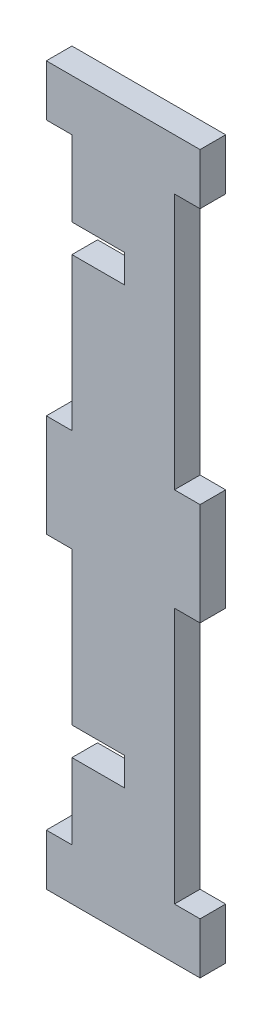
SolidWorks part; units mm, degrees
ref_plane "Front Plane" through (0, 0, 0) normal (0, 0, 1) x (1, 0, 0)
ref_plane "Top Plane" through (0, 0, 0) normal (0, 1, 0) x (1, 0, 0)
ref_plane "Right Plane" through (0, 0, 0) normal (1, 0, 0) x (0, 0, -1)
sketch "Model" plane through (0, 0, 0) normal (0, 0, 1) x (1, 0, 0)
  line L0 (-1086.4543, -202.297) -> (-1086.4543, -212.297)
  line L1 (-1091.4543, -202.297) -> (-1086.4543, -202.297)
  line L2 (-1086.4543, -132.297) -> (-1091.4543, -132.297)
  line L3 (-1116.4543, -212.297) -> (-1116.4543, -202.297)
  line L4 (-1086.4543, -212.297) -> (-1116.4543, -212.297)
  line L5 (-1091.4543, -152.297) -> (-1091.4543, -202.297)
  line L6 (-1086.4543, -152.297) -> (-1091.4543, -152.297)
  line L7 (-1086.4543, -132.297) -> (-1086.4543, -152.297)
  line L8 (-1091.4543, -132.297) -> (-1091.4544, -82.297)
  line L9 (-1091.4544, -82.297) -> (-1086.4544, -82.297)
  line L10 (-1086.4544, -82.297) -> (-1086.4544, -72.297)
  line L11 (-1086.4544, -72.297) -> (-1116.4544, -72.297)
  line L12 (-1116.4544, -72.297) -> (-1116.4544, -82.297)
  line L13 (-1116.4544, -82.297) -> (-1111.4544, -82.297)
  line L14 (-1111.4544, -82.297) -> (-1111.4544, -97.047)
  line L15 (-1101.2044, -97.047) -> (-1111.4544, -97.047)
  line L16 (-1101.2044, -102.547) -> (-1101.2044, -97.047)
  line L17 (-1111.4544, -102.547) -> (-1101.2044, -102.547)
  line L18 (-1111.4544, -102.547) -> (-1111.4543, -132.297)
  line L19 (-1111.4543, -132.297) -> (-1116.4543, -132.297)
  line L20 (-1116.4543, -132.297) -> (-1116.4543, -152.297)
  line L21 (-1111.4543, -152.297) -> (-1116.4543, -152.297)
  line L22 (-1111.4543, -182.047) -> (-1111.4543, -152.297)
  line L23 (-1111.4543, -182.047) -> (-1101.2043, -182.047)
  line L24 (-1101.2043, -182.047) -> (-1101.2043, -187.547)
  line L25 (-1101.2043, -187.547) -> (-1111.4543, -187.547)
  line L26 (-1111.4543, -202.297) -> (-1111.4543, -187.547)
  line L27 (-1116.4543, -202.297) -> (-1111.4543, -202.297)
  line L28 (-1109.4543, -207.297) -> (-1114.4543, -207.297)
  line L29 (-1112.4543, -206.297) -> (-1114.4543, -207.297)
  line L30 (-1112.4543, -208.297) -> (-1114.4543, -207.297)
  line L31 (-1108.4543, -210.3939) -> (-1105.9573, -211.0058)
  line L32 (-1104.1754, -204.7785) -> (-1104.2808, -205.1399)
  line L33 (-1104.5247, -206.337) -> (-1104.4353, -206.3979)
  line L34 (-1104.2777, -206.6414) -> (-1104.4353, -206.3979)
  line L35 (-1104.5249, -205.4413) -> (-1104.4361, -205.381)
  line L36 (-1104.1403, -204.3375) -> (-1104.1754, -204.7785)
  line L37 (-1104.1403, -209.27) -> (-1105.9573, -209.7445)
  line L38 (-1104.1747, -206.9973) -> (-1104.1403, -207.4406)
  line L39 (-1108.4482, -207.4406) -> (-1108.4123, -207.0067)
  line L40 (-1108.1486, -206.3979) -> (-1108.3047, -206.6414)
  line L41 (-1108.4482, -208.4584) -> (-1108.4482, -207.4406)
  line L42 (-1104.2777, -206.6414) -> (-1104.1747, -206.9973)
  line L43 (-1107.9675, -206.3167) -> (-1108.0611, -206.337)
  line L44 (-1104.1403, -207.4406) -> (-1104.1403, -208.4584)
  line L45 (-1107.9675, -206.3167) -> (-1104.6211, -206.3167)
  line L46 (-1104.4361, -205.381) -> (-1104.2808, -205.1399)
  line L47 (-1108.3047, -206.6414) -> (-1108.4123, -207.0067)
  line L48 (-1104.6211, -205.4614) -> (-1104.5249, -205.4413)
  line L49 (-1108.1486, -206.3979) -> (-1108.0611, -206.337)
  line L50 (-1108.4482, -208.4584) -> (-1104.1403, -208.4584)
  line L51 (-1105.9573, -209.7445) -> (-1108.4543, -210.3939)
  line L52 (-1105.9573, -209.7445) -> (-1105.9573, -211.0058)
  line L53 (-1104.6211, -206.3167) -> (-1104.5247, -206.337)
  line L54 (-1104.1754, -203.8965) -> (-1104.1403, -204.3375)
  line L55 (-1106.4279, -203.2337) -> (-1106.3317, -203.2136)
  line L56 (-1104.6211, -203.2136) -> (-1104.5249, -203.2337)
  line L57 (-1108.4482, -203.2885) -> (-1108.4482, -205.4614)
  line L58 (-1104.4361, -203.294) -> (-1104.2808, -203.5352)
  line L59 (-1104.5249, -203.2337) -> (-1104.4361, -203.294)
  line L60 (-1106.7126, -205.0119) -> (-1106.8125, -204.3375)
  line L61 (-1106.5167, -203.294) -> (-1106.4279, -203.2337)
  line L62 (-1108.4482, -205.4614) -> (-1106.3317, -205.4614)
  line L63 (-1106.7774, -203.8965) -> (-1106.672, -203.5352)
  line L64 (-1106.8125, -204.3375) -> (-1106.7774, -203.8965)
  line L65 (-1104.2808, -203.5352) -> (-1104.1754, -203.8965)
  line L66 (-1106.3317, -205.4614) -> (-1106.5862, -205.2429)
  line L67 (-1106.3317, -203.2136) -> (-1104.6211, -203.2136)
  line L68 (-1106.5862, -205.2429) -> (-1106.7126, -205.0119)
  line L69 (-1106.672, -203.5352) -> (-1106.5167, -203.294)
  line L70 (-1105.9573, -211.0058) -> (-1104.1403, -211.4553)
  line L71 (-1094.4895, -203.8246) -> (-1094.4543, -204.2656)
  line L72 (-1094.4543, -204.2656) -> (-1094.4895, -204.7066)
  line L73 (-1098.7684, -210.3159) -> (-1096.2713, -210.9278)
  line L74 (-1094.4543, -209.192) -> (-1096.2713, -209.6665)
  line L75 (-1096.2713, -209.6665) -> (-1096.2713, -210.9278)
  line L76 (-1096.2713, -209.6665) -> (-1098.7684, -210.3159)
  line L77 (-1096.9002, -205.171) -> (-1096.6457, -205.3895)
  line L78 (-1097.0266, -204.94) -> (-1097.1266, -204.2656)
  line L79 (-1098.7623, -205.3895) -> (-1098.7623, -203.2167)
  line L80 (-1094.8389, -205.3694) -> (-1094.7501, -205.3091)
  line L81 (-1094.5948, -205.068) -> (-1094.4895, -204.7066)
  line L82 (-1096.742, -203.1618) -> (-1096.8307, -203.2221)
  line L83 (-1096.8307, -203.2221) -> (-1096.9861, -203.4633)
  line L84 (-1096.6457, -205.3895) -> (-1098.7623, -205.3895)
  line L85 (-1094.8389, -205.3694) -> (-1094.9351, -205.3895)
  line L86 (-1094.5948, -205.068) -> (-1094.7501, -205.3091)
  line L87 (-1096.9002, -205.171) -> (-1097.0266, -204.94)
  line L88 (-1097.1266, -204.2656) -> (-1097.0914, -203.8246)
  line L89 (-1096.6457, -203.1417) -> (-1094.9351, -203.1417)
  line L90 (-1094.8389, -203.1618) -> (-1094.9351, -203.1417)
  line L91 (-1096.6457, -203.1417) -> (-1096.742, -203.1618)
  line L92 (-1096.9861, -203.4633) -> (-1097.0914, -203.8246)
  line L93 (-1096.2713, -210.9278) -> (-1094.4543, -211.3773)
  line L94 (-1094.7501, -203.2221) -> (-1094.5948, -203.4633)
  line L95 (-1094.5948, -203.4633) -> (-1094.4895, -203.8246)
  line L96 (-1094.8389, -203.1618) -> (-1094.7501, -203.2221)
  line L97 (-1096.2713, -207.9278) -> (-1094.4543, -208.3773)
  line L98 (-1096.2713, -206.6665) -> (-1098.7684, -207.3159)
  line L99 (-1098.7684, -207.3159) -> (-1096.2713, -207.9278)
  line L100 (-1094.4543, -206.192) -> (-1096.2713, -206.6665)
  line L101 (-1096.2713, -206.6665) -> (-1096.2713, -207.9278)
  line L102 (-1093.4543, -207.297) -> (-1088.4543, -207.297)
  line L103 (-1090.4543, -208.297) -> (-1088.4543, -207.297)
  line L104 (-1090.4543, -206.297) -> (-1088.4543, -207.297)
  line L105 (-1109.4544, -77.297) -> (-1114.4544, -77.297)
  line L106 (-1112.4544, -76.297) -> (-1114.4544, -77.297)
  line L107 (-1112.4544, -78.297) -> (-1114.4544, -77.297)
  line L108 (-1108.4544, -80.3939) -> (-1105.9573, -81.0058)
  line L109 (-1104.1755, -74.7785) -> (-1104.2808, -75.1399)
  line L110 (-1104.5247, -76.337) -> (-1104.4353, -76.3979)
  line L111 (-1104.2777, -76.6414) -> (-1104.4353, -76.3979)
  line L112 (-1104.5249, -75.4413) -> (-1104.4361, -75.381)
  line L113 (-1104.1403, -74.3375) -> (-1104.1755, -74.7785)
  line L114 (-1104.1403, -79.27) -> (-1105.9573, -79.7445)
  line L115 (-1104.1747, -76.9973) -> (-1104.1403, -77.4406)
  line L116 (-1108.4483, -77.4406) -> (-1108.4124, -77.0067)
  line L117 (-1108.1486, -76.3979) -> (-1108.3047, -76.6414)
  line L118 (-1108.4483, -78.4584) -> (-1108.4483, -77.4406)
  line L119 (-1104.2777, -76.6414) -> (-1104.1747, -76.9973)
  line L120 (-1107.9675, -76.3167) -> (-1108.0612, -76.337)
  line L121 (-1104.1403, -77.4406) -> (-1104.1403, -78.4584)
  line L122 (-1107.9675, -76.3167) -> (-1104.6211, -76.3167)
  line L123 (-1104.4361, -75.381) -> (-1104.2808, -75.1399)
  line L124 (-1108.3047, -76.6414) -> (-1108.4124, -77.0067)
  line L125 (-1104.6211, -75.4614) -> (-1104.5249, -75.4413)
  line L126 (-1108.1486, -76.3979) -> (-1108.0612, -76.337)
  line L127 (-1108.4483, -78.4584) -> (-1104.1403, -78.4584)
  line L128 (-1105.9573, -79.7445) -> (-1108.4544, -80.3939)
  line L129 (-1105.9573, -79.7445) -> (-1105.9573, -81.0058)
  line L130 (-1104.6211, -76.3167) -> (-1104.5247, -76.337)
  line L131 (-1104.1755, -73.8965) -> (-1104.1403, -74.3375)
  line L132 (-1106.4279, -73.2337) -> (-1106.3317, -73.2136)
  line L133 (-1104.6211, -73.2136) -> (-1104.5249, -73.2337)
  line L134 (-1108.4483, -73.2885) -> (-1108.4483, -75.4614)
  line L135 (-1104.4361, -73.294) -> (-1104.2808, -73.5352)
  line L136 (-1104.5249, -73.2337) -> (-1104.4361, -73.294)
  line L137 (-1106.7126, -75.0119) -> (-1106.8125, -74.3375)
  line L138 (-1106.5167, -73.294) -> (-1106.4279, -73.2337)
  line L139 (-1108.4483, -75.4614) -> (-1106.3317, -75.4614)
  line L140 (-1106.7774, -73.8965) -> (-1106.6721, -73.5352)
  line L141 (-1106.8125, -74.3375) -> (-1106.7774, -73.8965)
  line L142 (-1104.2808, -73.5352) -> (-1104.1755, -73.8965)
  line L143 (-1106.3317, -75.4614) -> (-1106.5862, -75.2429)
  line L144 (-1106.3317, -73.2136) -> (-1104.6211, -73.2136)
  line L145 (-1106.5862, -75.2429) -> (-1106.7126, -75.0119)
  line L146 (-1106.6721, -73.5352) -> (-1106.5167, -73.294)
  line L147 (-1105.9573, -81.0058) -> (-1104.1403, -81.4553)
  line L148 (-1094.4895, -73.8246) -> (-1094.4544, -74.2656)
  line L149 (-1094.4544, -74.2656) -> (-1094.4895, -74.7066)
  line L150 (-1098.7684, -80.3159) -> (-1096.2713, -80.9278)
  line L151 (-1094.4544, -79.192) -> (-1096.2713, -79.6665)
  line L152 (-1096.2713, -79.6665) -> (-1096.2713, -80.9278)
  line L153 (-1096.2713, -79.6665) -> (-1098.7684, -80.3159)
  line L154 (-1096.9002, -75.171) -> (-1096.6458, -75.3895)
  line L155 (-1097.0266, -74.94) -> (-1097.1266, -74.2656)
  line L156 (-1098.7623, -75.3895) -> (-1098.7623, -73.2167)
  line L157 (-1094.8389, -75.3694) -> (-1094.7501, -75.3091)
  line L158 (-1094.5948, -75.068) -> (-1094.4895, -74.7066)
  line L159 (-1096.742, -73.1618) -> (-1096.8308, -73.2221)
  line L160 (-1096.8308, -73.2221) -> (-1096.9861, -73.4633)
  line L161 (-1096.6458, -75.3895) -> (-1098.7623, -75.3895)
  line L162 (-1094.8389, -75.3694) -> (-1094.9351, -75.3895)
  line L163 (-1094.5948, -75.068) -> (-1094.7501, -75.3091)
  line L164 (-1096.9002, -75.171) -> (-1097.0266, -74.94)
  line L165 (-1097.1266, -74.2656) -> (-1097.0914, -73.8246)
  line L166 (-1096.6458, -73.1417) -> (-1094.9351, -73.1417)
  line L167 (-1094.8389, -73.1618) -> (-1094.9351, -73.1417)
  line L168 (-1096.6458, -73.1417) -> (-1096.742, -73.1618)
  line L169 (-1096.9861, -73.4633) -> (-1097.0914, -73.8246)
  line L170 (-1096.2713, -80.9278) -> (-1094.4544, -81.3773)
  line L171 (-1094.7501, -73.2221) -> (-1094.5948, -73.4633)
  line L172 (-1094.5948, -73.4633) -> (-1094.4895, -73.8246)
  line L173 (-1094.8389, -73.1618) -> (-1094.7501, -73.2221)
  line L174 (-1096.2713, -77.9278) -> (-1094.4544, -78.3773)
  line L175 (-1096.2713, -76.6665) -> (-1098.7684, -77.3159)
  line L176 (-1098.7684, -77.3159) -> (-1096.2713, -77.9278)
  line L177 (-1094.4544, -76.192) -> (-1096.2713, -76.6665)
  line L178 (-1096.2713, -76.6665) -> (-1096.2713, -77.9278)
  line L179 (-1093.4544, -77.297) -> (-1088.4544, -77.297)
  line L180 (-1090.4544, -78.297) -> (-1088.4544, -77.297)
  line L181 (-1090.4544, -76.297) -> (-1088.4544, -77.297)
  line L182 (-1094.2043, -99.797) -> (-1099.2043, -99.797)
  line L183 (-1097.2043, -98.797) -> (-1099.2043, -99.797)
  line L184 (-1097.2043, -100.797) -> (-1099.2043, -99.797)
  line L185 (-1096.027, -95.8622) -> (-1098.5184, -95.2503)
  line L186 (-1098.5184, -95.2503) -> (-1096.027, -94.6009)
  line L187 (-1096.027, -94.6009) -> (-1096.027, -95.8622)
  line L188 (-1094.2043, -94.1264) -> (-1098.5184, -95.2503)
  line L189 (-1098.5184, -95.2503) -> (-1094.2043, -96.3117)
  line L190 (-1094.2043, -96.3117) -> (-1096.0213, -95.8622)
  line L191 (-1096.0213, -95.8622) -> (-1096.0213, -94.6009)
  line L192 (-1096.0213, -94.6009) -> (-1094.2043, -94.1264)
  line L193 (-1094.2043, -89.1939) -> (-1094.2395, -89.6349)
  line L194 (-1094.2395, -89.6349) -> (-1094.3448, -89.9963)
  line L195 (-1094.3448, -89.9963) -> (-1094.5001, -90.2374)
  line L196 (-1094.5001, -90.2374) -> (-1094.5889, -90.2977)
  line L197 (-1094.5889, -90.2977) -> (-1094.6851, -90.3178)
  line L198 (-1094.6851, -90.3178) -> (-1094.5889, -90.2977)
  line L199 (-1094.5889, -90.2977) -> (-1094.5001, -90.2374)
  line L200 (-1094.5001, -90.2374) -> (-1094.3448, -89.9963)
  line L201 (-1094.3448, -89.9963) -> (-1094.2395, -89.6349)
  line L202 (-1094.2395, -88.7529) -> (-1094.3448, -88.3916)
  line L203 (-1094.3448, -88.3916) -> (-1094.5001, -88.1504)
  line L204 (-1094.5001, -88.1504) -> (-1094.5889, -88.0901)
  line L205 (-1094.5889, -88.0901) -> (-1094.6851, -88.07)
  line L206 (-1094.6851, -88.07) -> (-1096.3957, -88.07)
  line L207 (-1096.3957, -88.07) -> (-1096.492, -88.0901)
  line L208 (-1096.492, -88.0901) -> (-1096.5807, -88.1504)
  line L209 (-1096.5807, -88.1504) -> (-1096.7361, -88.3916)
  line L210 (-1096.7361, -88.3916) -> (-1096.8414, -88.7529)
  line L211 (-1096.8414, -88.7529) -> (-1096.8766, -89.1939)
  line L212 (-1096.8766, -89.1939) -> (-1096.7766, -89.8683)
  line L213 (-1096.7766, -89.8683) -> (-1096.6502, -90.0993)
  line L214 (-1096.6502, -90.0993) -> (-1096.3957, -90.3178)
  line L215 (-1096.3957, -90.3178) -> (-1098.5123, -90.3178)
  line L216 (-1098.5123, -90.3178) -> (-1098.5123, -88.1449)
  line L217 (-1098.5123, -88.1449) -> (-1098.5123, -90.3178)
  line L218 (-1098.5123, -90.3178) -> (-1096.3957, -90.3178)
  line L219 (-1096.3957, -90.3178) -> (-1096.6502, -90.0993)
  line L220 (-1096.6502, -90.0993) -> (-1096.7766, -89.8683)
  line L221 (-1096.7766, -89.8683) -> (-1096.8766, -89.1939)
  line L222 (-1096.8766, -89.1939) -> (-1096.8414, -88.7529)
  line L223 (-1096.8414, -88.7529) -> (-1096.7361, -88.3916)
  line L224 (-1096.7361, -88.3916) -> (-1096.5807, -88.1504)
  line L225 (-1096.5807, -88.1504) -> (-1096.492, -88.0901)
  line L226 (-1096.492, -88.0901) -> (-1096.3957, -88.07)
  line L227 (-1096.3957, -88.07) -> (-1094.6851, -88.07)
  line L228 (-1094.6851, -88.07) -> (-1094.5889, -88.0901)
  line L229 (-1094.5889, -88.0901) -> (-1094.5001, -88.1504)
  line L230 (-1094.5001, -88.1504) -> (-1094.3448, -88.3916)
  line L231 (-1094.3448, -88.3916) -> (-1094.2395, -88.7529)
  line L232 (-1094.2395, -88.7529) -> (-1094.2043, -89.1939)
  line L233 (-1094.2043, -93.3148) -> (-1096.4022, -93.3148)
  line L234 (-1096.4022, -93.3148) -> (-1096.4022, -92.297)
  line L235 (-1096.4022, -92.297) -> (-1096.3335, -91.7397)
  line L236 (-1096.3335, -91.7397) -> (-1096.2274, -91.4041)
  line L237 (-1096.2274, -91.4041) -> (-1096.0931, -91.2309)
  line L238 (-1098.5123, -92.297) -> (-1098.5123, -93.3148)
  line L239 (-1094.2043, -92.297) -> (-1094.2043, -93.3148)
  line L240 (-1094.3417, -91.504) -> (-1094.2387, -91.8646)
  line L241 (-1096.4658, -91.746) -> (-1096.4018, -92.297)
  line L242 (-1096.5706, -91.4041) -> (-1096.7095, -91.2309)
  line L243 (-1094.6851, -91.1731) -> (-1095.94, -91.1731)
  line L244 (-1094.2043, -92.297) -> (-1094.2387, -91.8646)
  line L245 (-1094.4962, -91.2558) -> (-1094.5864, -91.1938)
  line L246 (-1096.8639, -91.1731) -> (-1096.7093, -91.2309)
  line L247 (-1094.5864, -91.1938) -> (-1094.4963, -91.2558)
  line L248 (-1098.0315, -91.1731) -> (-1096.8639, -91.1731)
  line L249 (-1096.7093, -91.2309) -> (-1096.5704, -91.4041)
  line L250 (-1094.3417, -91.504) -> (-1094.4962, -91.2558)
  line L251 (-1098.1252, -91.1938) -> (-1098.2126, -91.2558)
  line L252 (-1094.2387, -91.8646) -> (-1094.3417, -91.504)
  line L253 (-1096.466, -91.746) -> (-1096.5706, -91.4041)
  line L254 (-1096.0929, -91.2309) -> (-1096.2272, -91.4041)
  line L255 (-1096.0931, -91.2309) -> (-1095.9401, -91.1731)
  line L256 (-1094.4963, -91.2558) -> (-1094.3417, -91.504)
  line L257 (-1098.3687, -91.504) -> (-1098.4764, -91.8677)
  line L258 (-1096.402, -92.297) -> (-1096.466, -91.746)
  line L259 (-1096.4018, -92.297) -> (-1096.4018, -93.3148)
  line L260 (-1098.5123, -92.297) -> (-1098.4764, -91.8677)
  line L261 (-1096.5704, -91.4041) -> (-1096.4658, -91.746)
  line L262 (-1098.4764, -91.8677) -> (-1098.5123, -92.297)
  line L263 (-1098.5123, -93.3148) -> (-1094.2043, -93.3148)
  line L264 (-1098.2126, -91.2558) -> (-1098.3687, -91.504)
  line L265 (-1098.3686, -91.504) -> (-1098.2125, -91.2558)
  line L266 (-1098.1251, -91.1938) -> (-1098.0315, -91.1731)
  line L267 (-1096.7095, -91.2309) -> (-1096.864, -91.1731)
  line L268 (-1094.6851, -91.1731) -> (-1094.5864, -91.1938)
  line L269 (-1095.9401, -91.1731) -> (-1094.6851, -91.1731)
  line L270 (-1096.2272, -91.4041) -> (-1096.3333, -91.7397)
  line L271 (-1096.4018, -93.3148) -> (-1098.5123, -93.3148)
  line L272 (-1098.2125, -91.2558) -> (-1098.1251, -91.1938)
  line L273 (-1096.3333, -91.7397) -> (-1096.402, -92.297)
  line L274 (-1094.2043, -93.3148) -> (-1094.2043, -92.297)
  line L275 (-1098.0315, -91.1731) -> (-1098.1252, -91.1938)
  line L276 (-1098.4764, -91.8677) -> (-1098.3686, -91.504)
  line L277 (-1094.5864, -91.1938) -> (-1094.6851, -91.1731)
  line L278 (-1095.94, -91.1731) -> (-1096.0929, -91.2309)
  line L279 (-1096.864, -91.1731) -> (-1098.0315, -91.1731)
  line L280 (-1098.5123, -93.3148) -> (-1098.5123, -92.297)
  line L281 (-1094.2387, -91.8646) -> (-1094.2043, -92.297)
  line L282 (-1096.027, -195.8622) -> (-1098.5184, -195.2503)
  line L283 (-1098.5184, -195.2503) -> (-1096.027, -194.6009)
  line L284 (-1096.027, -194.6009) -> (-1096.027, -195.8622)
  line L285 (-1094.2043, -194.1264) -> (-1098.5184, -195.2503)
  line L286 (-1098.5184, -195.2503) -> (-1094.2043, -196.3117)
  line L287 (-1094.2043, -196.3117) -> (-1096.0213, -195.8622)
  line L288 (-1096.0213, -195.8622) -> (-1096.0213, -194.6009)
  line L289 (-1096.0213, -194.6009) -> (-1094.2043, -194.1264)
  line L290 (-1094.2043, -189.1939) -> (-1094.2395, -189.6349)
  line L291 (-1094.2395, -189.6349) -> (-1094.3448, -189.9963)
  line L292 (-1094.3448, -189.9963) -> (-1094.5001, -190.2374)
  line L293 (-1094.5001, -190.2374) -> (-1094.5889, -190.2977)
  line L294 (-1094.5889, -190.2977) -> (-1094.6851, -190.3178)
  line L295 (-1094.6851, -190.3178) -> (-1094.5889, -190.2977)
  line L296 (-1094.5889, -190.2977) -> (-1094.5001, -190.2374)
  line L297 (-1094.5001, -190.2374) -> (-1094.3448, -189.9963)
  line L298 (-1094.3448, -189.9963) -> (-1094.2395, -189.6349)
  line L299 (-1094.2395, -188.7529) -> (-1094.3448, -188.3916)
  line L300 (-1094.3448, -188.3916) -> (-1094.5001, -188.1504)
  line L301 (-1094.5001, -188.1504) -> (-1094.5889, -188.0901)
  line L302 (-1094.5889, -188.0901) -> (-1094.6851, -188.07)
  line L303 (-1094.6851, -188.07) -> (-1096.3957, -188.07)
  line L304 (-1096.3957, -188.07) -> (-1096.492, -188.0901)
  line L305 (-1096.492, -188.0901) -> (-1096.5807, -188.1504)
  line L306 (-1096.5807, -188.1504) -> (-1096.7361, -188.3916)
  line L307 (-1096.7361, -188.3916) -> (-1096.8414, -188.7529)
  line L308 (-1096.8414, -188.7529) -> (-1096.8766, -189.1939)
  line L309 (-1096.8766, -189.1939) -> (-1096.7766, -189.8683)
  line L310 (-1096.7766, -189.8683) -> (-1096.6502, -190.0993)
  line L311 (-1096.6502, -190.0993) -> (-1096.3957, -190.3178)
  line L312 (-1096.3957, -190.3178) -> (-1098.5123, -190.3178)
  line L313 (-1098.5123, -190.3178) -> (-1098.5123, -188.1449)
  line L314 (-1098.5123, -188.1449) -> (-1098.5123, -190.3178)
  line L315 (-1098.5123, -190.3178) -> (-1096.3957, -190.3178)
  line L316 (-1096.3957, -190.3178) -> (-1096.6502, -190.0993)
  line L317 (-1096.6502, -190.0993) -> (-1096.7766, -189.8683)
  line L318 (-1096.7766, -189.8683) -> (-1096.8766, -189.1939)
  line L319 (-1096.8766, -189.1939) -> (-1096.8414, -188.7529)
  line L320 (-1096.8414, -188.7529) -> (-1096.7361, -188.3916)
  line L321 (-1096.7361, -188.3916) -> (-1096.5807, -188.1504)
  line L322 (-1096.5807, -188.1504) -> (-1096.492, -188.0901)
  line L323 (-1096.492, -188.0901) -> (-1096.3957, -188.07)
  line L324 (-1096.3957, -188.07) -> (-1094.6851, -188.07)
  line L325 (-1094.6851, -188.07) -> (-1094.5889, -188.0901)
  line L326 (-1094.5889, -188.0901) -> (-1094.5001, -188.1504)
  line L327 (-1094.5001, -188.1504) -> (-1094.3448, -188.3916)
  line L328 (-1094.3448, -188.3916) -> (-1094.2395, -188.7529)
  line L329 (-1094.2395, -188.7529) -> (-1094.2043, -189.1939)
  line L330 (-1094.2043, -193.3148) -> (-1096.4022, -193.3148)
  line L331 (-1096.4022, -193.3148) -> (-1096.4022, -192.297)
  line L332 (-1096.4022, -192.297) -> (-1096.3335, -191.7398)
  line L333 (-1096.3335, -191.7398) -> (-1096.2274, -191.4041)
  line L334 (-1096.2274, -191.4041) -> (-1096.0931, -191.2309)
  line L335 (-1098.5123, -192.297) -> (-1098.5123, -193.3148)
  line L336 (-1094.2043, -192.297) -> (-1094.2043, -193.3148)
  line L337 (-1094.3417, -191.504) -> (-1094.2387, -191.8646)
  line L338 (-1096.4658, -191.746) -> (-1096.4018, -192.297)
  line L339 (-1096.5706, -191.4041) -> (-1096.7095, -191.2309)
  line L340 (-1094.6851, -191.1731) -> (-1095.94, -191.1731)
  line L341 (-1094.2043, -192.297) -> (-1094.2387, -191.8646)
  line L342 (-1094.4962, -191.2558) -> (-1094.5864, -191.1938)
  line L343 (-1096.8639, -191.1731) -> (-1096.7093, -191.2309)
  line L344 (-1094.5864, -191.1938) -> (-1094.4963, -191.2558)
  line L345 (-1098.0315, -191.1731) -> (-1096.8639, -191.1731)
  line L346 (-1096.7093, -191.2309) -> (-1096.5704, -191.4041)
  line L347 (-1094.3417, -191.504) -> (-1094.4962, -191.2558)
  line L348 (-1098.1252, -191.1938) -> (-1098.2126, -191.2558)
  line L349 (-1094.2387, -191.8646) -> (-1094.3417, -191.504)
  line L350 (-1096.466, -191.746) -> (-1096.5706, -191.4041)
  line L351 (-1096.0929, -191.2309) -> (-1096.2272, -191.4041)
  line L352 (-1096.0931, -191.2309) -> (-1095.9401, -191.1731)
  line L353 (-1094.4963, -191.2558) -> (-1094.3417, -191.504)
  line L354 (-1098.3687, -191.504) -> (-1098.4764, -191.8677)
  line L355 (-1096.402, -192.297) -> (-1096.466, -191.746)
  line L356 (-1096.4018, -192.297) -> (-1096.4018, -193.3148)
  line L357 (-1098.5123, -192.297) -> (-1098.4764, -191.8677)
  line L358 (-1096.5704, -191.4041) -> (-1096.4658, -191.746)
  line L359 (-1098.4764, -191.8677) -> (-1098.5123, -192.297)
  line L360 (-1098.5123, -193.3148) -> (-1094.2043, -193.3148)
  line L361 (-1098.2126, -191.2558) -> (-1098.3687, -191.504)
  line L362 (-1098.3686, -191.504) -> (-1098.2125, -191.2558)
  line L363 (-1098.1251, -191.1938) -> (-1098.0315, -191.1731)
  line L364 (-1096.7095, -191.2309) -> (-1096.864, -191.1731)
  line L365 (-1094.6851, -191.1731) -> (-1094.5864, -191.1938)
  line L366 (-1095.9401, -191.1731) -> (-1094.6851, -191.1731)
  line L367 (-1096.2272, -191.4041) -> (-1096.3333, -191.7398)
  line L368 (-1096.4018, -193.3148) -> (-1098.5123, -193.3148)
  line L369 (-1098.2125, -191.2558) -> (-1098.1251, -191.1938)
  line L370 (-1096.3333, -191.7398) -> (-1096.402, -192.297)
  line L371 (-1094.2043, -193.3148) -> (-1094.2043, -192.297)
  line L372 (-1098.0315, -191.1731) -> (-1098.1252, -191.1938)
  line L373 (-1098.4764, -191.8677) -> (-1098.3686, -191.504)
  line L374 (-1094.5864, -191.1938) -> (-1094.6851, -191.1731)
  line L375 (-1095.94, -191.1731) -> (-1096.0929, -191.2309)
  line L376 (-1096.864, -191.1731) -> (-1098.0315, -191.1731)
  line L377 (-1098.5123, -193.3148) -> (-1098.5123, -192.297)
  line L378 (-1094.2387, -191.8646) -> (-1094.2043, -192.297)
  line L379 (-1094.2043, -184.797) -> (-1099.2043, -184.797)
  line L380 (-1097.2043, -183.797) -> (-1099.2043, -184.797)
  line L381 (-1097.2043, -185.797) -> (-1099.2043, -184.797)
  line L382 (-1109.4543, -142.297) -> (-1114.4543, -142.297)
  line L383 (-1112.4543, -141.297) -> (-1114.4543, -142.297)
  line L384 (-1112.4543, -143.297) -> (-1114.4543, -142.297)
  line L385 (-1108.4543, -145.3939) -> (-1105.9573, -146.0058)
  line L386 (-1104.1754, -139.7785) -> (-1104.2808, -140.1399)
  line L387 (-1104.5247, -141.337) -> (-1104.4353, -141.3979)
  line L388 (-1104.2777, -141.6414) -> (-1104.4353, -141.3979)
  line L389 (-1104.5249, -140.4413) -> (-1104.4361, -140.381)
  line L390 (-1104.1403, -139.3375) -> (-1104.1754, -139.7785)
  line L391 (-1104.1403, -144.27) -> (-1105.9573, -144.7445)
  line L392 (-1104.1747, -141.9973) -> (-1104.1403, -142.4406)
  line L393 (-1108.4483, -142.4406) -> (-1108.4124, -142.0067)
  line L394 (-1108.1486, -141.3979) -> (-1108.3047, -141.6414)
  line L395 (-1108.4483, -143.4584) -> (-1108.4483, -142.4406)
  line L396 (-1104.2777, -141.6414) -> (-1104.1747, -141.9973)
  line L397 (-1107.9675, -141.3167) -> (-1108.0612, -141.337)
  line L398 (-1104.1403, -142.4406) -> (-1104.1403, -143.4584)
  line L399 (-1107.9675, -141.3167) -> (-1104.6211, -141.3167)
  line L400 (-1104.4361, -140.381) -> (-1104.2808, -140.1399)
  line L401 (-1108.3047, -141.6414) -> (-1108.4124, -142.0067)
  line L402 (-1104.6211, -140.4614) -> (-1104.5249, -140.4413)
  line L403 (-1108.1486, -141.3979) -> (-1108.0612, -141.337)
  line L404 (-1108.4483, -143.4584) -> (-1104.1403, -143.4584)
  line L405 (-1105.9573, -144.7445) -> (-1108.4543, -145.3939)
  line L406 (-1105.9573, -144.7445) -> (-1105.9573, -146.0058)
  line L407 (-1104.6211, -141.3167) -> (-1104.5247, -141.337)
  line L408 (-1104.1754, -138.8965) -> (-1104.1403, -139.3375)
  line L409 (-1106.4279, -138.2337) -> (-1106.3317, -138.2136)
  line L410 (-1104.6211, -138.2136) -> (-1104.5249, -138.2337)
  line L411 (-1108.4483, -138.2885) -> (-1108.4483, -140.4614)
  line L412 (-1104.4361, -138.294) -> (-1104.2808, -138.5352)
  line L413 (-1104.5249, -138.2337) -> (-1104.4361, -138.294)
  line L414 (-1106.7126, -140.0119) -> (-1106.8125, -139.3375)
  line L415 (-1106.5167, -138.294) -> (-1106.4279, -138.2337)
  line L416 (-1108.4483, -140.4614) -> (-1106.3317, -140.4614)
  line L417 (-1106.7774, -138.8965) -> (-1106.6721, -138.5352)
  line L418 (-1106.8125, -139.3375) -> (-1106.7774, -138.8965)
  line L419 (-1104.2808, -138.5352) -> (-1104.1754, -138.8965)
  line L420 (-1106.3317, -140.4614) -> (-1106.5862, -140.2429)
  line L421 (-1106.3317, -138.2136) -> (-1104.6211, -138.2136)
  line L422 (-1106.5862, -140.2429) -> (-1106.7126, -140.0119)
  line L423 (-1106.6721, -138.5352) -> (-1106.5167, -138.294)
  line L424 (-1105.9573, -146.0058) -> (-1104.1403, -146.4553)
  line L425 (-1094.4895, -138.8246) -> (-1094.4543, -139.2656)
  line L426 (-1094.4543, -139.2656) -> (-1094.4895, -139.7066)
  line L427 (-1098.7684, -145.3159) -> (-1096.2713, -145.9278)
  line L428 (-1094.4543, -144.192) -> (-1096.2713, -144.6665)
  line L429 (-1096.2713, -144.6665) -> (-1096.2713, -145.9278)
  line L430 (-1096.2713, -144.6665) -> (-1098.7684, -145.3159)
  line L431 (-1096.9002, -140.171) -> (-1096.6458, -140.3895)
  line L432 (-1097.0266, -139.94) -> (-1097.1266, -139.2656)
  line L433 (-1098.7623, -140.3895) -> (-1098.7623, -138.2167)
  line L434 (-1094.8389, -140.3694) -> (-1094.7501, -140.3091)
  line L435 (-1094.5948, -140.068) -> (-1094.4895, -139.7066)
  line L436 (-1096.742, -138.1618) -> (-1096.8308, -138.2221)
  line L437 (-1096.8308, -138.2221) -> (-1096.9861, -138.4633)
  line L438 (-1096.6458, -140.3895) -> (-1098.7623, -140.3895)
  line L439 (-1094.8389, -140.3694) -> (-1094.9351, -140.3895)
  line L440 (-1094.5948, -140.068) -> (-1094.7501, -140.3091)
  line L441 (-1096.9002, -140.171) -> (-1097.0266, -139.94)
  line L442 (-1097.1266, -139.2656) -> (-1097.0914, -138.8246)
  line L443 (-1096.6458, -138.1417) -> (-1094.9351, -138.1417)
  line L444 (-1094.8389, -138.1618) -> (-1094.9351, -138.1417)
  line L445 (-1096.6458, -138.1417) -> (-1096.742, -138.1618)
  line L446 (-1096.9861, -138.4633) -> (-1097.0914, -138.8246)
  line L447 (-1096.2713, -145.9278) -> (-1094.4543, -146.3773)
  line L448 (-1094.7501, -138.2221) -> (-1094.5948, -138.4633)
  line L449 (-1094.5948, -138.4633) -> (-1094.4895, -138.8246)
  line L450 (-1094.8389, -138.1618) -> (-1094.7501, -138.2221)
  line L451 (-1096.2713, -142.9278) -> (-1094.4543, -143.3773)
  line L452 (-1096.2713, -141.6665) -> (-1098.7684, -142.3159)
  line L453 (-1098.7684, -142.3159) -> (-1096.2713, -142.9278)
  line L454 (-1094.4543, -141.192) -> (-1096.2713, -141.6665)
  line L455 (-1096.2713, -141.6665) -> (-1096.2713, -142.9278)
  line L456 (-1093.4543, -142.297) -> (-1088.4543, -142.297)
  line L457 (-1090.4543, -143.297) -> (-1088.4543, -142.297)
  line L458 (-1090.4543, -141.297) -> (-1088.4543, -142.297)
  line L459 (-1097.3263, -172.7921) -> (-1096.265, -172.7921)
  line L460 (-1095.1723, -174.8682) -> (-1097.3263, -174.8682)
  line L461 (-1097.3263, -174.8682) -> (-1097.3263, -174.3374)
  line L462 (-1096.2805, -165.6735) -> (-1097.3263, -165.6735)
  line L463 (-1096.265, -173.9098) -> (-1096.265, -172.7921)
  line L464 (-1097.3263, -175.4083) -> (-1097.3263, -174.8682)
  line L465 (-1096.265, -173.9098) -> (-1097.3263, -173.9098)
  line L466 (-1095.1723, -173.9098) -> (-1096.265, -173.9098)
  line L467 (-1095.1723, -172.4113) -> (-1097.3293, -172.4113)
  line L468 (-1095.3202, -171.8711) -> (-1095.3646, -171.9013)
  line L469 (-1095.3646, -171.9013) -> (-1095.4127, -171.9113)
  line L470 (-1096.1754, -170.8094) -> (-1096.2657, -170.8908)
  line L471 (-1096.4985, -171.8992) -> (-1096.4499, -171.8629)
  line L472 (-1095.1899, -171.5699) -> (-1095.1723, -171.3494)
  line L473 (-1095.4127, -171.9113) -> (-1095.5657, -171.9113)
  line L474 (-1096.2657, -170.8908) -> (-1096.3205, -171.0256)
  line L475 (-1095.2426, -171.7506) -> (-1095.1899, -171.5699)
  line L476 (-1097.134, -170.7975) -> (-1097.1784, -170.8276)
  line L477 (-1095.3202, -171.8711) -> (-1095.2426, -171.7506)
  line L478 (-1097.3087, -171.1289) -> (-1097.3263, -171.3494)
  line L479 (-1096.5521, -171.9113) -> (-1096.4985, -171.8992)
  line L480 (-1097.0859, -171.9113) -> (-1097.134, -171.9013)
  line L481 (-1096.4499, -171.8629) -> (-1096.3679, -171.7178)
  line L482 (-1097.134, -171.9013) -> (-1097.1784, -171.8711)
  line L483 (-1096.3398, -171.2136) -> (-1096.3205, -171.0256)
  line L484 (-1096.1754, -170.8094) -> (-1096.0495, -170.7812)
  line L485 (-1097.0859, -171.9113) -> (-1096.5521, -171.9113)
  line L486 (-1095.2426, -170.9482) -> (-1095.1899, -171.1289)
  line L487 (-1096.0495, -170.7812) -> (-1095.4127, -170.7874)
  line L488 (-1097.3087, -171.1289) -> (-1097.2561, -170.9482)
  line L489 (-1097.3087, -171.5699) -> (-1097.3263, -171.3494)
  line L490 (-1096.3484, -171.5543) -> (-1096.3398, -171.2136)
  line L491 (-1095.1723, -171.3494) -> (-1095.1899, -171.1289)
  line L492 (-1097.134, -170.7975) -> (-1097.0859, -170.7874)
  line L493 (-1096.3679, -171.7178) -> (-1096.3484, -171.5543)
  line L494 (-1097.3087, -171.5699) -> (-1097.2561, -171.7506)
  line L495 (-1095.2426, -170.9482) -> (-1095.3202, -170.8276)
  line L496 (-1095.3202, -170.8276) -> (-1095.3646, -170.7975)
  line L497 (-1095.3646, -170.7975) -> (-1095.4127, -170.7874)
  line L498 (-1097.2561, -171.7506) -> (-1097.1784, -171.8711)
  line L499 (-1097.1784, -170.8276) -> (-1097.2561, -170.9482)
  line L500 (-1096.933, -170.7874) -> (-1097.0859, -170.7874)
  line L501 (-1095.4127, -168.0435) -> (-1095.3646, -168.0536)
  line L502 (-1095.3646, -168.0536) -> (-1095.3202, -168.0837)
  line L503 (-1095.1723, -168.6055) -> (-1095.1899, -168.826)
  line L504 (-1095.3646, -169.1574) -> (-1095.3202, -169.1272)
  line L505 (-1096.1754, -168.0655) -> (-1096.2657, -168.1469)
  line L506 (-1097.1784, -168.0837) -> (-1097.134, -168.0536)
  line L507 (-1095.4127, -169.1674) -> (-1095.3646, -169.1574)
  line L508 (-1096.1754, -168.0655) -> (-1096.0495, -168.0373)
  line L509 (-1097.1784, -169.1272) -> (-1097.2561, -169.0067)
  line L510 (-1096.3484, -168.8104) -> (-1096.3679, -168.9739)
  line L511 (-1096.4499, -169.119) -> (-1096.3679, -168.9739)
  line L512 (-1095.2426, -169.0067) -> (-1095.1899, -168.826)
  line L513 (-1095.4127, -168.0435) -> (-1096.0495, -168.0373)
  line L514 (-1096.3398, -168.4697) -> (-1096.3205, -168.2817)
  line L515 (-1095.1899, -168.385) -> (-1095.2426, -168.2043)
  line L516 (-1096.3398, -168.4697) -> (-1096.3484, -168.8104)
  line L517 (-1097.2561, -168.2043) -> (-1097.3087, -168.385)
  line L518 (-1095.1723, -168.6055) -> (-1095.1899, -168.385)
  line L519 (-1096.5521, -169.1674) -> (-1097.0859, -169.1674)
  line L520 (-1096.2657, -168.1469) -> (-1096.3205, -168.2817)
  line L521 (-1097.134, -169.1574) -> (-1097.1784, -169.1272)
  line L522 (-1097.0859, -168.0435) -> (-1097.134, -168.0536)
  line L523 (-1096.4985, -169.1553) -> (-1096.5521, -169.1674)
  line L524 (-1095.2426, -168.2043) -> (-1095.3202, -168.0837)
  line L525 (-1097.0859, -169.1674) -> (-1097.134, -169.1574)
  line L526 (-1095.3202, -169.1272) -> (-1095.2426, -169.0067)
  line L527 (-1096.933, -168.0435) -> (-1097.0859, -168.0435)
  line L528 (-1097.1784, -168.0837) -> (-1097.2561, -168.2043)
  line L529 (-1097.3087, -168.385) -> (-1097.3263, -168.6055)
  line L530 (-1097.3263, -168.6055) -> (-1097.3087, -168.826)
  line L531 (-1097.3087, -168.826) -> (-1097.2561, -169.0067)
  line L532 (-1096.4985, -169.1553) -> (-1096.4499, -169.119)
  line L533 (-1095.3646, -161.8127) -> (-1095.3202, -161.8429)
  line L534 (-1097.3263, -164.6089) -> (-1097.3263, -165.6735)
  line L535 (-1095.4127, -160.3042) -> (-1097.3171, -160.3042)
  line L536 (-1097.2545, -166.2635) -> (-1097.3083, -166.4461)
  line L537 (-1097.3263, -167.172) -> (-1095.1723, -167.172)
  line L538 (-1097.1327, -166.1113) -> (-1097.0859, -166.1012)
  line L539 (-1097.1765, -166.1418) -> (-1097.2545, -166.2635)
  line L540 (-1095.1723, -165.6735) -> (-1095.1723, -164.6089)
  line L541 (-1095.241, -166.2635) -> (-1095.1895, -166.4415)
  line L542 (-1097.1327, -166.1113) -> (-1097.1765, -166.1418)
  line L543 (-1095.3646, -161.8127) -> (-1095.4127, -161.8027)
  line L544 (-1095.3198, -166.1418) -> (-1095.3645, -166.1113)
  line L545 (-1095.1723, -165.6735) -> (-1096.2805, -165.6735)
  line L546 (-1095.241, -166.2635) -> (-1095.3198, -166.1418)
  line L547 (-1095.1895, -166.4415) -> (-1095.1723, -166.6631)
  line L548 (-1097.3083, -166.4461) -> (-1097.3263, -166.6631)
  line L549 (-1096.2805, -165.6735) -> (-1096.2805, -164.7588)
  line L550 (-1097.3263, -167.172) -> (-1097.3263, -166.6631)
  line L551 (-1095.3645, -166.1113) -> (-1095.4127, -166.1012)
  line L552 (-1095.1723, -167.172) -> (-1095.1723, -166.6631)
  line L553 (-1095.4127, -169.1674) -> (-1095.5657, -169.1674)
  line L554 (-1097.3293, -167.672) -> (-1095.1723, -167.672)
  line L555 (-1097.0859, -166.1012) -> (-1095.4127, -166.1012)
  line L556 (-1097.2561, -162.7658) -> (-1097.3087, -162.5851)
  line L557 (-1097.134, -162.9165) -> (-1097.1784, -162.8864)
  line L558 (-1097.1784, -162.8864) -> (-1097.2561, -162.7658)
  line L559 (-1097.3087, -162.5851) -> (-1097.3263, -162.3646)
  line L560 (-1095.3646, -162.9165) -> (-1095.4127, -162.9266)
  line L561 (-1095.3202, -161.3879) -> (-1095.3646, -161.4181)
  line L562 (-1095.2426, -161.9634) -> (-1095.1899, -162.1441)
  line L563 (-1095.3646, -160.3142) -> (-1095.4127, -160.3042)
  line L564 (-1097.3263, -162.3646) -> (-1097.3087, -162.1441)
  line L565 (-1095.3202, -162.8864) -> (-1095.3646, -162.9165)
  line L566 (-1097.2561, -161.9634) -> (-1097.1784, -161.8429)
  line L567 (-1095.2426, -162.7658) -> (-1095.3202, -162.8864)
  line L568 (-1097.0859, -162.9266) -> (-1097.134, -162.9165)
  line L569 (-1095.3202, -161.8429) -> (-1095.2426, -161.9634)
  line L570 (-1095.1899, -162.1441) -> (-1095.1723, -162.3646)
  line L571 (-1095.4127, -161.4281) -> (-1097.3171, -161.4281)
  line L572 (-1095.3646, -160.3142) -> (-1095.3202, -160.3444)
  line L573 (-1095.3646, -161.4181) -> (-1095.4127, -161.4281)
  line L574 (-1096.265, -172.7921) -> (-1095.1723, -172.7921)
  line L575 (-1095.1899, -161.0866) -> (-1095.2426, -161.2673)
  line L576 (-1097.3263, -159.9296) -> (-1097.3263, -159.3895)
  line L577 (-1095.4127, -162.9266) -> (-1097.0859, -162.9266)
  line L578 (-1095.1723, -160.8661) -> (-1095.1899, -160.6457)
  line L579 (-1095.1899, -162.5851) -> (-1095.2426, -162.7658)
  line L580 (-1097.3087, -162.1441) -> (-1097.2561, -161.9634)
  line L581 (-1095.1723, -159.3895) -> (-1097.3263, -159.3895)
  line L582 (-1095.1723, -162.3646) -> (-1095.1899, -162.5851)
  line L583 (-1097.3263, -159.3895) -> (-1097.3263, -158.8588)
  line L584 (-1095.1723, -160.8661) -> (-1095.1899, -161.0866)
  line L585 (-1097.1784, -161.8429) -> (-1097.134, -161.8127)
  line L586 (-1097.134, -161.8127) -> (-1097.0859, -161.8027)
  line L587 (-1095.3202, -160.3444) -> (-1095.2426, -160.465)
  line L588 (-1097.0859, -161.8027) -> (-1095.4127, -161.8027)
  line L589 (-1095.3202, -161.3879) -> (-1095.2426, -161.2673)
  line L590 (-1095.1899, -160.6457) -> (-1095.2426, -160.465)
  line L591 (-1100.0954, -158.9016) -> (-1099.9179, -159.0222)
  line L592 (-1107.8704, -166.2231) -> (-1107.9421, -167.091)
  line L593 (-1102.9603, -171.911) -> (-1102.9717, -174.4336)
  line L594 (-1107.1679, -164.8837) -> (-1107.3428, -165.0055)
  line L595 (-1099.3263, -161.1093) -> (-1099.3965, -161.9912)
  line L596 (-1099.3965, -160.2273) -> (-1099.3263, -161.1093)
  line L597 (-1104.6005, -160.2273) -> (-1104.3897, -159.5046)
  line L598 (-1102.9717, -174.4336) -> (-1099.3263, -175.3327)
  line L599 (-1107.8704, -166.2231) -> (-1107.655, -165.4926)
  line L600 (-1107.1679, -164.8837) -> (-1106.9806, -164.8432)
  line L601 (-1107.3428, -165.0055) -> (-1107.655, -165.4926)
  line L602 (-1106.3688, -164.8432) -> (-1106.9806, -164.8432)
  line L603 (-1107.349, -169.1796) -> (-1107.1726, -169.299)
  line L604 (-1102.9603, -171.911) -> (-1107.9543, -173.2098)
  line L605 (-1100.2878, -164.8432) -> (-1100.8997, -164.8432)
  line L606 (-1099.9101, -169.1796) -> (-1099.601, -168.7019)
  line L607 (-1099.9163, -165.0055) -> (-1100.095, -164.8837)
  line L608 (-1099.601, -165.4926) -> (-1099.9163, -165.0055)
  line L609 (-1103.7091, -158.8615) -> (-1103.9015, -158.9016)
  line L610 (-1099.6073, -159.5046) -> (-1099.9179, -159.0222)
  line L611 (-1099.3263, -167.091) -> (-1099.395, -166.2043)
  line L612 (-1099.3263, -170.962) -> (-1102.9603, -171.911)
  line L613 (-1107.9543, -173.2098) -> (-1102.9717, -174.4336)
  line L614 (-1107.8704, -167.9683) -> (-1107.655, -168.7019)
  line L615 (-1099.601, -168.7019) -> (-1099.395, -167.9807)
  line L616 (-1099.395, -166.2043) -> (-1099.601, -165.4926)
  line L617 (-1107.655, -168.7019) -> (-1107.349, -169.1796)
  line L618 (-1099.6073, -159.5046) -> (-1099.3965, -160.2273)
  line L619 (-1099.9179, -163.1963) -> (-1099.6073, -162.714)
  line L620 (-1104.6005, -160.2273) -> (-1104.6707, -161.1093)
  line L621 (-1106.9806, -169.3388) -> (-1100.2878, -169.3388)
  line L622 (-1103.9015, -158.9016) -> (-1104.0791, -159.0222)
  line L623 (-1099.395, -167.9807) -> (-1099.3263, -167.091)
  line L624 (-1100.2878, -158.8615) -> (-1103.7091, -158.8615)
  line L625 (-1107.1726, -169.299) -> (-1106.9806, -169.3388)
  line L626 (-1100.2878, -158.8615) -> (-1100.0954, -158.9016)
  line L627 (-1099.3965, -161.9912) -> (-1099.6073, -162.714)
  line L628 (-1100.2878, -169.3388) -> (-1100.0904, -169.299)
  line L629 (-1103.7091, -163.3571) -> (-1107.9421, -163.3571)
  line L630 (-1107.9421, -167.091) -> (-1107.8704, -167.9683)
  line L631 (-1099.9179, -163.1963) -> (-1100.0954, -163.3169)
  line L632 (-1104.4709, -162.458) -> (-1104.218, -162.92)
  line L633 (-1103.7091, -163.3571) -> (-1104.218, -162.92)
  line L634 (-1104.3897, -159.5046) -> (-1104.0791, -159.0222)
  line L635 (-1107.9421, -159.0113) -> (-1107.9421, -163.3571)
  line L636 (-1100.2878, -163.3571) -> (-1100.0954, -163.3169)
  line L637 (-1100.095, -164.8837) -> (-1100.2878, -164.8432)
  line L638 (-1100.0904, -169.299) -> (-1099.9101, -169.1796)
  line L639 (-1104.6707, -161.1093) -> (-1104.4709, -162.458)
  line L640 (-1098.3263, -175.3327) -> (-1098.3263, -159.0113)
sketch "Sketch2" plane through (0, 0, 0) normal (0, 0, 1) x (1, 0, 0)
  line L0 (-1086.4543, -212.297) -> (-1116.4543, -212.297) construction
  line L1 (-1086.4543, -202.297) -> (-1086.4543, -212.297) construction
  line L2 (-1091.4543, -202.297) -> (-1086.4543, -202.297) construction
  line L3 (-1091.4543, -152.297) -> (-1091.4543, -202.297) construction
  line L4 (-1086.4543, -152.297) -> (-1091.4543, -152.297) construction
  line L5 (-1086.4543, -132.297) -> (-1086.4543, -152.297) construction
  line L6 (-1086.4543, -132.297) -> (-1091.4543, -132.297) construction
  line L7 (-1091.4543, -132.297) -> (-1091.4544, -82.297) construction
  line L8 (-1091.4544, -82.297) -> (-1086.4544, -82.297) construction
  line L9 (-1086.4544, -82.297) -> (-1086.4544, -72.297) construction
  line L10 (-1086.4544, -72.297) -> (-1116.4544, -72.297) construction
  line L11 (-1116.4544, -72.297) -> (-1116.4544, -82.297) construction
  line L12 (-1116.4544, -82.297) -> (-1111.4544, -82.297) construction
  line L13 (-1111.4544, -82.297) -> (-1111.4544, -97.047) construction
  line L14 (-1101.2044, -97.047) -> (-1111.4544, -97.047) construction
  line L15 (-1101.2044, -102.547) -> (-1101.2044, -97.047) construction
  line L16 (-1111.4544, -102.547) -> (-1101.2044, -102.547) construction
  line L17 (-1111.4544, -102.547) -> (-1111.4543, -132.297) construction
  line L18 (-1111.4543, -132.297) -> (-1116.4543, -132.297) construction
  line L19 (-1116.4543, -132.297) -> (-1116.4543, -152.297) construction
  line L20 (-1111.4543, -152.297) -> (-1116.4543, -152.297) construction
  line L21 (-1111.4543, -182.047) -> (-1111.4543, -152.297) construction
  line L22 (-1111.4543, -182.047) -> (-1101.2043, -182.047) construction
  line L23 (-1101.2043, -182.047) -> (-1101.2043, -187.547) construction
  line L24 (-1101.2043, -187.547) -> (-1111.4543, -187.547) construction
  line L25 (-1111.4543, -202.297) -> (-1111.4543, -187.547) construction
  line L26 (-1116.4543, -202.297) -> (-1111.4543, -202.297) construction
  line L27 (-1116.4543, -212.297) -> (-1116.4543, -202.297) construction
  line L28 (-1086.4543, -212.297) -> (-1116.4543, -212.297)
  line L29 (-1086.4543, -202.297) -> (-1086.4543, -212.297)
  line L30 (-1091.4543, -202.297) -> (-1086.4543, -202.297)
  line L31 (-1091.4543, -152.297) -> (-1091.4543, -202.297)
  line L32 (-1086.4543, -152.297) -> (-1091.4543, -152.297)
  line L33 (-1086.4543, -132.297) -> (-1086.4543, -152.297)
  line L34 (-1086.4543, -132.297) -> (-1091.4543, -132.297)
  line L35 (-1091.4543, -132.297) -> (-1091.4544, -82.297)
  line L36 (-1091.4544, -82.297) -> (-1086.4544, -82.297)
  line L37 (-1086.4544, -82.297) -> (-1086.4544, -72.297)
  line L38 (-1086.4544, -72.297) -> (-1116.4544, -72.297)
  line L39 (-1116.4544, -72.297) -> (-1116.4544, -82.297)
  line L40 (-1116.4544, -82.297) -> (-1111.4544, -82.297)
  line L41 (-1111.4544, -82.297) -> (-1111.4544, -97.047)
  line L42 (-1101.2044, -97.047) -> (-1111.4544, -97.047)
  line L43 (-1101.2044, -102.547) -> (-1101.2044, -97.047)
  line L44 (-1111.4544, -102.547) -> (-1101.2044, -102.547)
  line L45 (-1111.4544, -102.547) -> (-1111.4543, -132.297)
  line L46 (-1111.4543, -132.297) -> (-1116.4543, -132.297)
  line L47 (-1116.4543, -132.297) -> (-1116.4543, -152.297)
  line L48 (-1111.4543, -152.297) -> (-1116.4543, -152.297)
  line L49 (-1111.4543, -182.047) -> (-1111.4543, -152.297)
  line L50 (-1111.4543, -182.047) -> (-1101.2043, -182.047)
  line L51 (-1101.2043, -182.047) -> (-1101.2043, -187.547)
  line L52 (-1101.2043, -187.547) -> (-1111.4543, -187.547)
  line L53 (-1111.4543, -202.297) -> (-1111.4543, -187.547)
  line L54 (-1116.4543, -202.297) -> (-1111.4543, -202.297)
  line L55 (-1116.4543, -212.297) -> (-1116.4543, -202.297)
  line L56 (-1116.4543, -142.297) -> (-1127.4798, -142.297) construction
extrude "Boss-Extrude1" add sketch "Sketch2" along normal mid plane 5
ref_plane "Plane1" through (0, -142.297, 0) normal (0, 1, 0) x (1, 0, 0)
